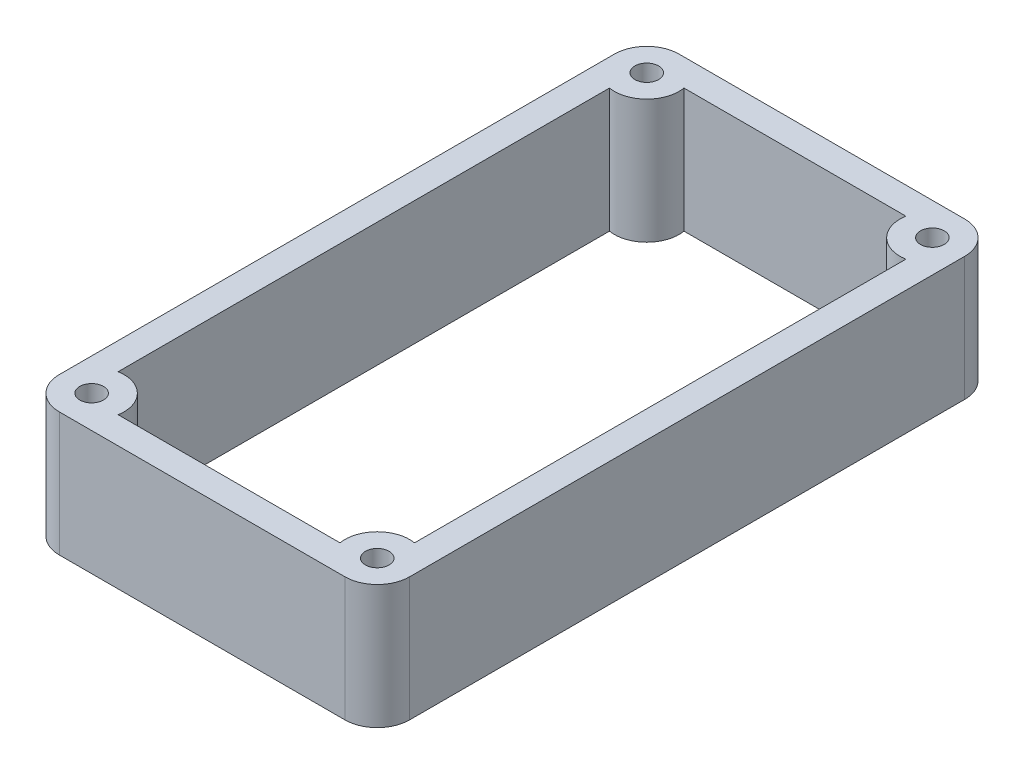
SolidWorks part; units mm, degrees
ref_plane "Front Plane" through (0, 0, 0) normal (0, 0, 1) x (1, 0, 0)
ref_plane "Top Plane" through (0, 0, 0) normal (0, 1, 0) x (1, 0, 0)
ref_plane "Right Plane" through (0, 0, 0) normal (1, 0, 0) x (0, 0, -1)
sketch "Sketch1" plane through (0, 0, 0) normal (0, 1, 0) x (1, 0, 0)
  line L1 (-32.5, -57.5) -> (32.5, -57.5)
  line L2 (-32.5, -57.5) -> (-32.5, 57.5)
  line L3 (-32.5, 57.5) -> (32.5, 57.5)
  line L4 (32.5, -57.5) -> (32.5, 57.5)
  line L5 (0, 57.5) -> (0, -57.5) construction
  line L6 (-32.5, 0) -> (32.5, 0) construction
  line L7 (-27.5, 52.5) -> (27.5, 52.5)
  line L8 (-27.5, 52.5) -> (-27.5, -52.5)
  line L9 (-27.5, -52.5) -> (27.5, -52.5)
  line L10 (27.5, 52.5) -> (27.5, -52.5)
  line L11 (0, -52.5) -> (0, 52.5) construction
  line L12 (-27.5, 0) -> (27.5, 0) construction
  point P0 (0, 0)
  point P4 (0, 0)
  dimension "D1" = 115
  dimension "D2" = 65
  dimension "D3" = 5
  dimension "D4" = 5
extrude "Boss-Extrude1" add sketch "Sketch1" along normal blind 23
fillet "Fillet1" radius 6 4 edges at (32.5, 11.5, -57.5) (-32.5, 11.5, -57.5) (-32.5, 11.5, 57.5) (32.5, 11.5, 57.5)
sketch "Sketch2" plane through (0, 23, 0) normal (0, 1, 0) x (1, 0, 0)
  circle A0 centre (-26.5, 51.5) radius 6
  circle A1 centre (26.5, 51.5) radius 6
  circle A2 centre (-26.5, -51.5) radius 6
  circle A3 centre (26.5, -51.5) radius 6
  dimension "D1" = 12
extrude "Boss-Extrude2" add sketch "Sketch2" against normal up to surface (23 mm away) up to face at (0, 0, 0)
sketch "Sketch4" plane through (0, 23, 0) normal (0, 1, 0) x (1, 0, 0)
  circle A0 centre (-26.5, 51.5) radius 2.2
  circle A1 centre (26.5, 51.5) radius 2.2
  circle A2 centre (26.5, -51.5) radius 2.2
  circle A3 centre (-26.5, -51.5) radius 2.2
  dimension "D1" = 4.4
extrude "Cut-Extrude1" cut sketch "Sketch4" against normal blind 23
